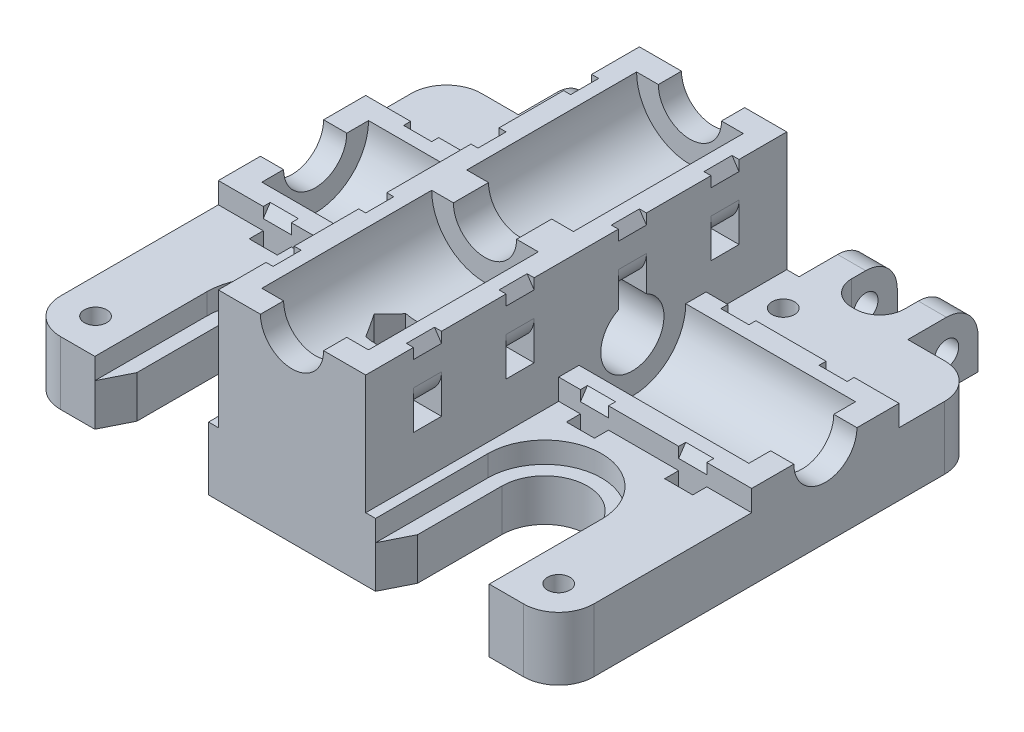
SolidWorks part; units mm, degrees
material "ABS"
ref_plane "Front Plane" through (0, 0, 0) normal (0, 0, 1) x (1, 0, 0)
ref_plane "Top Plane" through (0, 0, 0) normal (0, 1, 0) x (1, 0, 0)
ref_plane "Right Plane" through (0, 0, 0) normal (1, 0, 0) x (0, 0, -1)
sketch "Sketch1" plane through (0, 0, 0) normal (0, 1, 0) x (1, 0, 0)
  line L0 (0, 0) -> (-38, 0)
  line L1 (-38, 0) -> (-38, 21)
  line L2 (-38, 21) -> (38, 21)
  line L3 (38, 21) -> (38, 0)
  line L4 (38, 0) -> (0, 0)
  line L5 (-23, 10.5) -> (-35.5, 10.5) construction
  line L6 (-35.5, 10.5) -> (-38, 10.5) construction
  line L7 (-35.5, 2.5) -> (-10.5, 2.5) construction
  line L8 (-35.5, 2.5) -> (-35.5, 18.5) construction
  line L9 (-35.5, 18.5) -> (-10.5, 18.5) construction
  line L10 (-10.5, 2.5) -> (-10.5, 18.5) construction
  line L11 (-35.5, 2.5) -> (-10.5, 18.5) construction
  line L12 (-35.5, 18.5) -> (-10.5, 2.5) construction
  line L13 (35.5, 2.5) -> (10.5, 2.5) construction
  line L14 (35.5, 2.5) -> (35.5, 18.5) construction
  line L15 (35.5, 18.5) -> (10.5, 18.5) construction
  line L16 (10.5, 2.5) -> (10.5, 18.5) construction
  line L17 (35.5, 2.5) -> (10.5, 18.5) construction
  line L18 (35.5, 18.5) -> (10.5, 2.5) construction
  line L19 (23, 10.5) -> (35.5, 10.5) construction
  line L20 (35.5, 10.5) -> (38, 10.5) construction
  line L21 (-23, 18.5) -> (-23, 21) construction
  line L22 (-23, 2.5) -> (-23, 0) construction
  line L23 (23, 18.5) -> (23, 21) construction
  line L24 (23, 2.5) -> (23, 0) construction
  line L25 (-8, 21) -> (-8, 0) construction
  line L26 (8, 21) -> (8, 0) construction
  line L27 (0, 21) -> (0, 0) construction
  line L28 (-10.5, 10.5) -> (-8, 10.5) construction
  line L29 (-8, 10.5) -> (0, 10.5) construction
  line L30 (0, 10.5) -> (8, 10.5) construction
  line L31 (8, 10.5) -> (10.5, 10.5) construction
  point P8 (-23, 10.5)
  point P13 (23, 10.5)
  dimension "D1" = 16
  dimension "D2" = 2.5
  dimension "D3" = 25
  dimension "D4" = 16
extrude "Boss-Extrude1" add sketch "Sketch1" along normal blind 12
sketch "Sketch5" plane through (0, 12, 0) normal (0, 1, 0) x (1, 0, 0)
  line L0 (0, 32.5) -> (0, 21) construction
  line L1 (10.5, -27.5) -> (38, -27.5) construction
  line L2 (-10.5, 32.5) -> (10.5, 32.5)
  line L3 (38, -27.5) -> (38, 0) construction
  line L4 (38, 21) -> (-38, 21) construction
  line L5 (0, 21) -> (0, 0) construction
  line L6 (-10.5, 32.5) -> (-10.5, -27.5)
  line L7 (-10.5, -27.5) -> (10.5, -27.5)
  line L8 (10.5, -27.5) -> (10.5, 32.5)
  dimension "D1" = 60
extrude "Boss-Extrude4" add sketch "Sketch5" along normal blind 14 and the other way up to surface other way up to face at (0, 0, -10.5)
sketch "Sketch6" plane through (0, 12, 0) normal (0, 1, 0) x (1, 0, 0)
  line L0 (-38, 10.5) -> (38, 10.5)
  line L1 (-38, 21) -> (-38, 0) construction
  line L2 (38, 0) -> (38, 21) construction
  line L3 (-38, 10.5) -> (-38, 15)
  line L4 (-38, 15) -> (-34.7, 15)
  line L5 (-34.7, 15) -> (-34.7, 18.1)
  line L6 (10.5, 18.1) -> (34.7, 18.1)
  line L14 (-34.7, 18.1) -> (-10.5, 18.1)
  line L15 (-10.5, 0) -> (-10.5, 21) construction
  line L16 (-10.5, 18.1) -> (-10.5, 15)
  line L17 (-10.5, 15) -> (10.5, 15)
  line L18 (10.5, -27.5) -> (10.5, 32.5) construction
  line L19 (10.5, 15) -> (10.5, 18.1)
  line L29 (34.7, 18.1) -> (34.7, 15)
  line L30 (34.7, 15) -> (38, 15)
  line L31 (38, 15) -> (38, 10.5)
  line L32 (-10.5, 32.5) -> (-10.5, -27.5) construction
  line L33 (-48.6063, 10.5) -> (50.7164, 10.5) construction
  dimension "D1" = 9
  dimension "D2" = 15.2
  dimension "D5" = 24.2
revolve "Cut-Revolve1" cut sketch "Sketch6" angle 360 about L33
sketch "Sketch7" plane through (0, 26, 0) normal (0, 1, 0) x (1, 0, 0)
  line L0 (0, 32.5) -> (0, -27.5)
  line L1 (10.5, 32.5) -> (-10.5, 32.5) construction
  line L2 (-10.5, -27.5) -> (10.5, -27.5) construction
  line L3 (0, -27.5) -> (4.5, -27.5)
  line L4 (4.5, -27.5) -> (4.5, -24.2)
  line L5 (4.5, -24.2) -> (7.6, -24.2)
  line L6 (7.6, 0) -> (7.6, -24.2)
  line L7 (7.6, 5) -> (7.6, 29.2)
  line L15 (7.6, 0) -> (4.5, 0)
  line L16 (4.5, 0) -> (4.5, 5)
  line L17 (4.5, 5) -> (7.6, 5)
  line L27 (7.6, 29.2) -> (4.5, 29.2)
  line L28 (4.5, 29.2) -> (4.5, 32.5)
  line L29 (4.5, 32.5) -> (0, 32.5)
  line L33 (-38, 6) -> (-34.7, 6) construction
  line L35 (-34.7, 18.1) -> (-34.7, 15) construction
  line L36 (0, 39.3952) -> (0, -36.9972) construction
  dimension "D1" = 15.2
  dimension "D2" = 24.2
revolve "Cut-Revolve2" cut sketch "Sketch7" angle 360 about L36
sketch "Sketch8" plane through (0, 0, 0) normal (0, -1, 0) x (1, 0, 0)
  line L1 (-10.5, 0) -> (-38, 0)
  line L2 (-10.5, 0) -> (-10.5, 27.5)
  line L3 (-10.5, 27.5) -> (-38, 27.5)
  line L4 (-38, 0) -> (-38, 27.5)
  line L5 (10.5, 0) -> (38, 0)
  line L6 (10.5, 0) -> (10.5, 27.5)
  line L7 (10.5, 27.5) -> (38, 27.5)
  line L8 (38, 0) -> (38, 27.5)
  line L9 (10.5, -21) -> (38, -21)
  line L10 (10.5, -21) -> (10.5, -32.5)
  line L11 (10.5, -32.5) -> (38, -32.5)
  line L12 (38, -21) -> (38, -32.5)
  line L13 (-10.5, -21) -> (-38, -21)
  line L14 (-10.5, -21) -> (-10.5, -32.5)
  line L15 (-10.5, -32.5) -> (-38, -32.5)
  line L16 (-38, -21) -> (-38, -32.5)
  line L17 (-38, -21) -> (-38, 0) construction
  line L18 (-10.5, 27.5) -> (10.5, 27.5) construction
  line L19 (38, 0) -> (38, -21) construction
  line L20 (10.5, -32.5) -> (-10.5, -32.5) construction
extrude "Boss-Extrude5" add sketch "Sketch8" against normal blind 9
sketch "Sketch9" plane through (0, 9, 0) normal (0, 1, 0) x (1, 0, 0)
  line L0 (0, 0) -> (0, -27.5) construction
  line L2 (-4.5, -27.5) -> (4.5, -27.5) construction
  line L3 (0, -11.5) -> (38, -11.5) construction
  line L5 (11.9, -11.5) -> (11.9, -27.5)
  line L6 (11.9, -27.5) -> (28.1, -27.5)
  line L7 (28.1, -27.5) -> (28.1, -11.5)
  line L8 (38, -27.5) -> (10.5, -27.5) construction
  line L9 (38, 0) -> (38, -27.5) construction
  arc A0 (28.1, -11.5) -> (11.9, -11.5) centre (20, -11.5) ccw
  dimension "D1" = 16.2
  dimension "D2" = 40
  dimension "D3" = 16
extrude "Cut-Extrude2" cut sketch "Sketch9" against normal offset from surface (3 mm away) 6 up to face at (0, 0, -2.5)
sketch "Sketch10" plane through (0, 6, 0) normal (0, 1, 0) x (1, 0, 0)
  line L0 (13.9, -11.5) -> (13.9, -23.5)
  line L2 (13.9, -23.5) -> (11.9, -27.5)
  line L3 (26.1, -23.5) -> (26.1, -11.5)
  line L4 (11.9, -27.5) -> (28.1, -27.5)
  line L5 (28.1, -27.5) -> (26.1, -23.5)
  line L6 (13.9, -23.5) -> (26.1, -23.5) construction
  arc A0 (26.1, -11.5) -> (13.9, -11.5) centre (20, -11.5) ccw
  dimension "D1" = 12.2
  dimension "D2" = 4
extrude "Cut-Extrude3" cut sketch "Sketch10" against normal through all
mirror "Mirror1" about plane through (0, 0, 0) normal (1, 0, 0) of "Cut-Extrude3", "Cut-Extrude2"
fillet "Fillet1" radius 5 4 edges at (-38, 4.5, 27.5) (38, 4.5, 27.5) (38, 4.5, -32.5) (-38, 4.5, -32.5)
sketch "Sketch11" plane through (0, 9, 0) normal (0, 1, 0) x (1, 0, 0)
  line L0 (-33, 27.5) -> (-15, 27.5) construction
  line L1 (-15, 27.5) -> (15, 27.5) construction
  line L2 (15, 27.5) -> (33, 27.5) construction
  circle A0 centre (33, -22.5) radius 1.6
  circle A1 centre (15, 27.5) radius 1.6
  circle A2 centre (-15, 27.5) radius 1.6
  circle A3 centre (-33, -22.5) radius 1.6
  dimension "D1" = 3.2
  dimension "D2" = 30
extrude "Cut-Extrude4" cut sketch "Sketch11" against normal through all
sketch "Sketch12" plane through (0, 0, 0) normal (0, -1, 0) x (1, 0, 0)
  line L0 (0, -32.5) -> (0, -17.5) construction
  line L1 (33, -32.5) -> (-33, -32.5) construction
  line L2 (0, -17.5) -> (0, 0) construction
  line L3 (0, 0) -> (0, 12.5) construction
  line L4 (0, 12.5) -> (0, 27.5) construction
  line L5 (-11.9, 27.5) -> (11.9, 27.5) construction
  circle A0 centre (0, 12.5) radius 1.6
  circle A2 centre (15, -27.5) radius 1.6 construction
  dimension "D1" = 15
extrude "Cut-Extrude5" cut sketch "Sketch12" against normal through all
sketch "Sketch13" plane through (0, 26, 0) normal (0, 1, 0) x (1, 0, 0)
  line L7 (3.2909, -12.5) -> (1.6454, -9.65)
  line L8 (1.6454, -9.65) -> (-1.6454, -9.65)
  line L9 (-1.6454, -9.65) -> (-3.2909, -12.5)
  line L10 (-3.2909, -12.5) -> (-1.6454, -15.35)
  line L11 (-1.6454, -15.35) -> (1.6454, -15.35)
  line L12 (1.6454, -15.35) -> (3.2909, -12.5)
  circle A1 centre (0, -12.5) radius 2.85 construction
  dimension "D1" = 5.7
extrude "Cut-Extrude6" cut sketch "Sketch13" against normal up to surface (17 mm away) up to face at (15, 9, -25.9)
sketch "Sketch15" plane through (0, 9, 0) normal (0, 1, 0) x (1, 0, 0)
  line L0 (20, -11.5) -> (20, 32.5) construction
  line L1 (10.5, 32.5) -> (33, 32.5) construction
  line L2 (20, 32.5) -> (23.75, 32.5) construction
  line L3 (23.75, 32.5) -> (23.75, 42.5)
  line L4 (23.75, 42.5) -> (27.75, 42.5)
  line L5 (27.75, 42.5) -> (27.75, 32.5)
  line L6 (27.75, 32.5) -> (23.75, 32.5)
  line L7 (20, 32.5) -> (16.25, 32.5) construction
  line L8 (16.25, 32.5) -> (16.25, 42.5)
  line L9 (16.25, 42.5) -> (12.25, 42.5)
  line L10 (12.25, 42.5) -> (12.25, 32.5)
  line L11 (12.25, 32.5) -> (16.25, 32.5)
  dimension "D1" = 15.5
  dimension "D2" = 4
  dimension "D3" = 10
extrude "Boss-Extrude7" add sketch "Sketch15" against normal up to surface (9 mm away) up to face at (0, 0, 10.9)
fillet "Fillet2" radius 4.5 2 edges at (14.25, 9, -42.5) (25.75, 9, -42.5)
fillet "Fillet3" radius 3.5 2 edges at (16.25, 4.5, -32.5) (23.75, 4.5, -32.5)
mirror "Mirror2" about plane through (0, 0, 0) normal (1, 0, 0) of "Fillet3", "Fillet2", "Boss-Extrude7"
sketch "Sketch17" plane through (27.75, 0, 0) normal (1, 0, 0) x (0, 0, -1)
  line L0 (42.5, 4.5) -> (38, 4.5) construction
  circle A0 centre (38, 4.5) radius 1.75
  dimension "D1" = 3.5
  dimension "D2" = 4.5
extrude "Cut-Extrude7" cut sketch "Sketch17" against normal up to surface (55.5 mm away) up to face at (-27.75, 4.6864, -37.7864)
sketch "Sketch18" plane through (0, 9, 0) normal (0, 1, 0) x (1, 0, 0)
  line L0 (10.5, 0) -> (38, 0) construction
  line L1 (13.6, 0) -> (17.6, 0)
  line L2 (13.6, 0) -> (13.6, -2)
  line L3 (13.6, -2) -> (17.6, -2)
  line L4 (17.6, 0) -> (17.6, -2)
  line L5 (10.5, 0) -> (38, 0) construction
  line L6 (27.6, 0) -> (31.6, 0)
  line L7 (27.6, 0) -> (27.6, -2)
  line L8 (27.6, -2) -> (31.6, -2)
  line L9 (31.6, 0) -> (31.6, -2)
  line L10 (38, 21) -> (10.5, 21) construction
  line L11 (31.6, 21) -> (27.6, 21)
  line L12 (31.6, 21) -> (31.6, 23)
  line L13 (31.6, 23) -> (27.6, 23)
  line L14 (27.6, 21) -> (27.6, 23)
  line L15 (13.6, 21) -> (13.6, 0) construction
  line L16 (17.6, 21) -> (13.6, 21)
  line L17 (17.6, 21) -> (17.6, 23)
  line L18 (17.6, 23) -> (13.6, 23)
  line L19 (13.6, 21) -> (13.6, 23)
  line L20 (17.6, -2) -> (27.6, -2) construction
  line L21 (31.6, 0) -> (31.6, 21) construction
  line L22 (27.6, 23) -> (17.6, 23) construction
  line L23 (10.5, 10.5) -> (34.7, 10.5) construction
  line L26 (22.6, 23) -> (22.6, 10.5) construction
  line L27 (10.5, -27.5) -> (10.5, 32.5) construction
  line L28 (34.7, 18.1) -> (34.7, 2.9) construction
  dimension "D1" = 4
  dimension "D2" = 2
  dimension "D3" = 18
extrude "Cut-Extrude8" cut sketch "Sketch18" against normal through all
sketch "Sketch19" plane through (0, 0, -21) normal (0, 0, -1) x (-1, 0, 0)
  line L0 (-27.6, 0) -> (-31.6, 0) construction
  line L1 (-31.6, 0) -> (-27.6, 0)
  line L2 (-31.6, 0) -> (-31.6, 2)
  line L3 (-31.6, 2) -> (-27.6, 2)
  line L4 (-27.6, 0) -> (-27.6, 2)
  line L5 (-27.6, 0) -> (-27.6, 9) construction
  line L6 (-13.6, 0) -> (-13.6, 9) construction
  line L7 (-17.6, 0) -> (-13.6, 0)
  line L8 (-17.6, 0) -> (-17.6, 2)
  line L9 (-17.6, 2) -> (-13.6, 2)
  line L10 (-13.6, 0) -> (-13.6, 2)
  dimension "D1" = 2
extrude "Cut-Extrude9" cut sketch "Sketch19" against normal up to surface (21 mm away) up to face at (-24.25, 10.5, 0)
fillet "Fillet4" radius 5 4 edges at (29.6, 2, -21) (29.6, 2, 0) (15.6, 2, -21) (15.6, 2, 0)
mirror "Mirror4" about plane through (0, 0, 0) normal (1, 0, 0) of "Fillet4", "Cut-Extrude9", "Cut-Extrude8"
sketch "Sketch20" plane through (10.5, 0, 0) normal (1, 0, 0) x (0, 0, -1)
  line L0 (-24.2, 26) -> (-24.2, 16.5) construction
  line L1 (-27.5, 26) -> (32.5, 26) construction
  line L2 (-24.2, 16.5) -> (-18.7, 16.5) construction
  line L3 (-18.7, 16.5) -> (-5.5, 16.5) construction
  line L4 (0, 16.5) -> (0, 26) construction
  line L5 (-5.5, 16.5) -> (0, 16.5) construction
  line L6 (0, 16.5) -> (5, 16.5) construction
  line L7 (-20.7, 15.5) -> (-16.7, 15.5)
  line L8 (-20.7, 15.5) -> (-20.7, 17.5)
  line L9 (-20.7, 17.5) -> (-16.7, 17.5)
  line L10 (-16.7, 15.5) -> (-16.7, 17.5)
  line L11 (-20.7, 15.5) -> (-16.7, 17.5) construction
  line L12 (-20.7, 17.5) -> (-16.7, 15.5) construction
  line L13 (-7.5, 15.5) -> (-3.5, 15.5)
  line L14 (-7.5, 15.5) -> (-7.5, 17.5)
  line L15 (-7.5, 17.5) -> (-3.5, 17.5)
  line L16 (-3.5, 15.5) -> (-3.5, 17.5)
  line L17 (-7.5, 15.5) -> (-3.5, 17.5) construction
  line L18 (-7.5, 17.5) -> (-3.5, 15.5) construction
  line L19 (5, 16.5) -> (5, 26) construction
  line L20 (5, 16.5) -> (10.5, 16.5) construction
  line L21 (10.5, 16.5) -> (23.7, 16.5) construction
  line L22 (23.7, 16.5) -> (29.2, 16.5) construction
  line L23 (29.2, 16.5) -> (29.2, 26) construction
  line L25 (8.5, 15.5) -> (12.5, 15.5)
  line L26 (8.5, 15.5) -> (8.5, 17.5)
  line L27 (8.5, 17.5) -> (12.5, 17.5)
  line L28 (12.5, 15.5) -> (12.5, 17.5)
  line L29 (8.5, 15.5) -> (12.5, 17.5) construction
  line L30 (8.5, 17.5) -> (12.5, 15.5) construction
  line L31 (21.7, 15.5) -> (25.7, 15.5)
  line L32 (21.7, 15.5) -> (21.7, 17.5)
  line L33 (21.7, 17.5) -> (25.7, 17.5)
  line L34 (25.7, 15.5) -> (25.7, 17.5)
  line L35 (21.7, 15.5) -> (25.7, 17.5) construction
  line L36 (21.7, 17.5) -> (25.7, 15.5) construction
  dimension "D1" = 5.5
  dimension "D2" = 4
  dimension "D3" = 2
  dimension "D4" = 8.5
extrude "Cut-Extrude13" cut sketch "Sketch20" against normal up to surface (21 mm away) up to face at (-10.5, 12.84, -7.3)
fillet "Fillet5" radius 3.5 8 edges at (-10.5, 17.5, -23.7) (-10.5, 17.5, -10.5) (-10.5, 17.5, 5.5) (-10.5, 17.5, 18.7) (10.5, 17.5, -23.7) (10.5, 17.5, -10.5) (10.5, 17.5, 5.5) (10.5, 17.5, 18.7)
sketch "Sketch21" plane through (0, 0, 16.7) normal (0, 0, 1) x (1, 0, 0)
  line L0 (9.5, 26) -> (10.5, 24.5)
  line L1 (4.5, 26) -> (10.5, 26) construction
  line L2 (10.5, 9) -> (10.5, 26) construction
  line L3 (10.5, 24.5) -> (10.5, 26)
  line L4 (10.5, 26) -> (9.5, 26)
  dimension "D1" = 1
  dimension "D2" = 1.5
extrude "Cut-Extrude14" cut sketch "Sketch21" along normal up to surface (4 mm away) up to face at (0, 17.7584, 20.7)
sketch "Sketch22" plane through (0, 0, 3.5) normal (0, 0, 1) x (1, 0, 0)
  line L0 (10.5, 26) -> (9.5, 26)
  line L1 (4.5, 26) -> (10.5, 26) construction
  line L2 (9.5, 26) -> (10.5, 24.5)
  line L3 (10.5, 9) -> (10.5, 26) construction
  line L4 (10.5, 24.5) -> (10.5, 26) construction
  line L5 (10.5, 24.5) -> (10.5, 26)
  line L7 (10.5, 26) -> (9.5, 26) construction
extrude "Cut-Extrude15" cut sketch "Sketch22" along normal up to surface (4 mm away) up to face at (0, 17.7584, 7.5)
ref_plane "Plane1" through (0, 0, -2.5) normal (0, 0, -1) x (-1, 0, 0)
mirror "Mirror5" about plane through (0, 0, 0) normal (1, 0, 0) of "Cut-Extrude15", "Cut-Extrude14"
mirror "Mirror7" about plane through (0, 0, -2.5) normal (0, 0, -1) of "Mirror5", "Cut-Extrude15", "Cut-Extrude14"
sketch "Sketch23" plane through (13.6, 0, 0) normal (1, 0, 0) x (0, 0, -1)
  line L0 (0, 12) -> (0, 10.5)
  line L1 (0, 12) -> (0, 9) construction
  line L2 (0, 10.5) -> (1, 12)
  line L3 (0, 12) -> (6, 12) construction
  line L4 (1, 12) -> (0, 12)
  dimension "D1" = 1
  dimension "D2" = 1.5
extrude "Cut-Extrude16" cut sketch "Sketch23" along normal up to surface (4 mm away) up to face at (17.6, 5.1929, -10.5)
sketch "Sketch24" plane through (27.6, 0, 0) normal (1, 0, 0) x (0, 0, -1)
  line L0 (0, 12) -> (0, 10.5)
  line L1 (0, 12) -> (0, 9) construction
  line L2 (0, 10.5) -> (1, 12)
  line L3 (2.9, 12) -> (0, 12) construction
  line L4 (1, 12) -> (0, 12)
  line L5 (1, 12) -> (0, 12) construction
  line L6 (0, 12) -> (0, 10.5) construction
extrude "Cut-Extrude17" cut sketch "Sketch24" along normal up to surface (4 mm away) up to face at (31.6, 5.1929, -10.5)
ref_plane "Plane2" through (0, 0, -10.5) normal (0, 0, 1) x (1, 0, 0)
mirror "Mirror8" about plane through (0, 0, -10.5) normal (0, 0, 1) of "Cut-Extrude16", "Cut-Extrude17"
mirror "Mirror9" about plane through (0, 0, 0) normal (1, 0, 0) of "Mirror8", "Cut-Extrude16", "Cut-Extrude17"
fillet "Fillet6" [suppressed] radius 1.5
